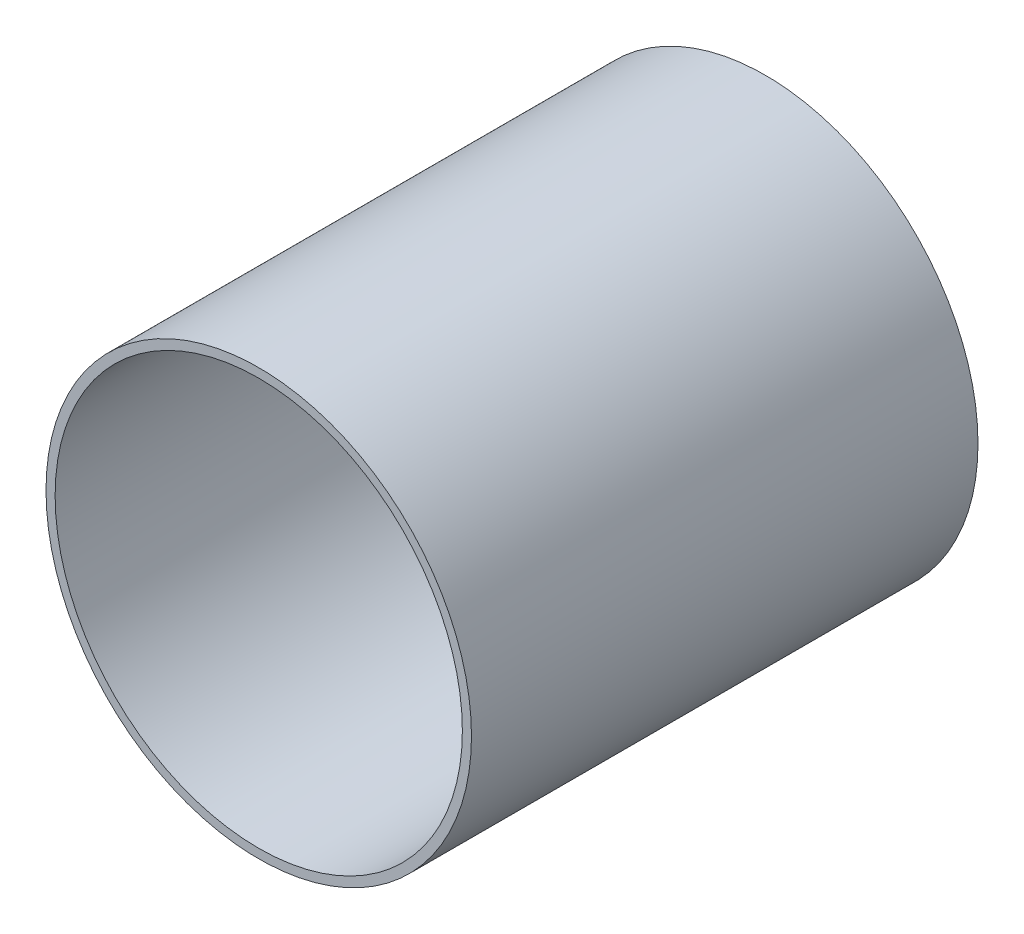
SolidWorks part; units mm, degrees
ref_plane "Front Plane" through (0, 0, 0) normal (0, 0, 1) x (1, 0, 0)
ref_plane "Top Plane" through (0, 0, 0) normal (0, 1, 0) x (1, 0, 0)
ref_plane "Right Plane" through (0, 0, 0) normal (1, 0, 0) x (0, 0, -1)
sketch "Sketch1" plane through (0, 0, 0) normal (0, 0, 1) x (1, 0, 0)
  circle A0 centre (0, 0) radius 10.05
  circle A1 centre (0, 0) radius 10.5
  dimension "D1" = 21
  dimension "D2" = 20.1
extrude "Boss-Extrude1" add sketch "Sketch1" along normal blind 25
